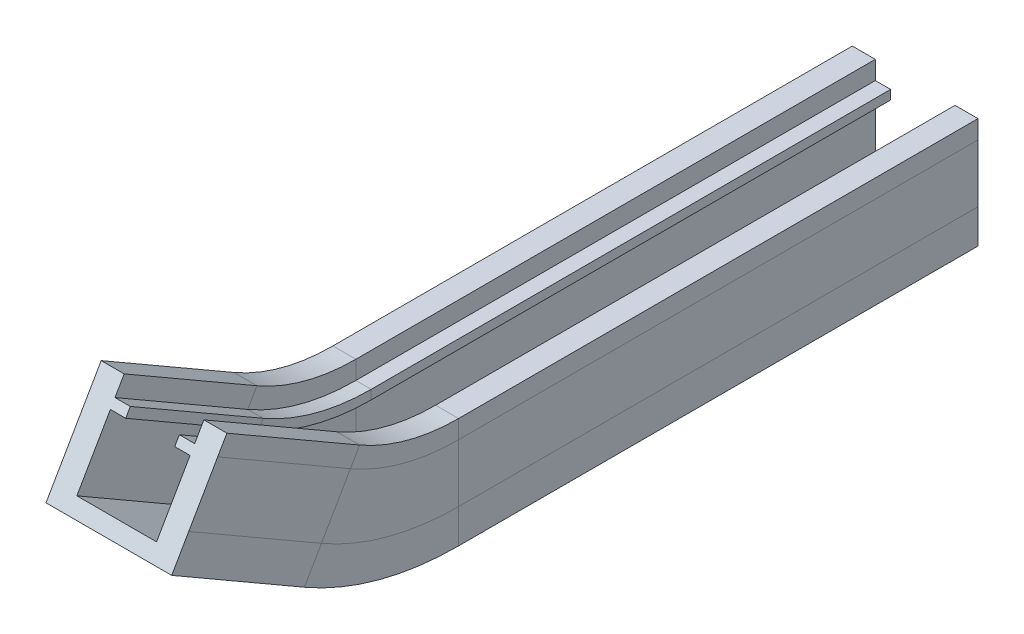
SolidWorks part; units mm, degrees
ref_plane "前视基准面" through (0, 0, 0) normal (0, 0, 1) x (1, 0, 0)
ref_plane "上视基准面" through (0, 0, 0) normal (0, 1, 0) x (1, 0, 0)
ref_plane "右视基准面" through (0, 0, 0) normal (1, 0, 0) x (0, 0, -1)
sketch "草图2" plane through (0, 0, 0) normal (0, 0, 1) x (1, 0, 0)
  line L0 (0, 0) -> (0, -86.0436) construction
  line L1 (-41, -55.4123) -> (-41, -77.6359)
  line L2 (16, -17.6359) -> (26, -17.6359)
  line L3 (41, -17.6359) -> (41, -55.4123)
  line L4 (41, -55.4123) -> (41, -77.6359)
  line L5 (41, -77.6359) -> (-41, -77.6359)
  line L6 (16, -17.6359) -> (16, -23.6359)
  line L7 (16, -23.6359) -> (26, -23.6359)
  line L8 (26, -23.6359) -> (26, -67.3843)
  line L9 (26, -67.3843) -> (-26, -67.3843)
  line L10 (-26, -23.6359) -> (-26, -67.3843)
  line L11 (-16, -23.6359) -> (-26, -23.6359)
  line L12 (-16, -17.6359) -> (-16, -23.6359)
  line L13 (-41, -17.6359) -> (-41, -55.4123)
  line L14 (-16, -17.6359) -> (-26, -17.6359)
  line L15 (-41, -17.6359) -> (-41, -5.6359)
  line L16 (-41, -5.6359) -> (-26, -5.6359)
  line L17 (-26, -5.6359) -> (-26, -17.6359)
  line L18 (26, -5.6359) -> (26, -17.6359)
  line L19 (41, -5.6359) -> (26, -5.6359)
  line L20 (41, -17.6359) -> (41, -5.6359)
  point P13 (0, -77.6359)
  point P15 (0, -67.3843)
  dimension "D1" = 60
sketch "草图3" plane through (0, 0, 0) normal (1, 0, 0) x (0, 0, -1)
  line L0 (0, -36.5241) -> (-338.8835, -36.5241)
  line L1 (0, -17.6359) -> (0, -55.4123) construction
  line L2 (-418.8835, -15.0882) -> (-505.486, 34.9118)
  arc A0 (-338.8835, -36.5241) -> (-418.8835, -15.0882) centre (-338.8835, 123.4759) cw
  dimension "D1" = 160
  dimension "D2" = 100
  dimension "D3" = 150
sweep "扫描2" add profiles "草图2" path "草图3"
